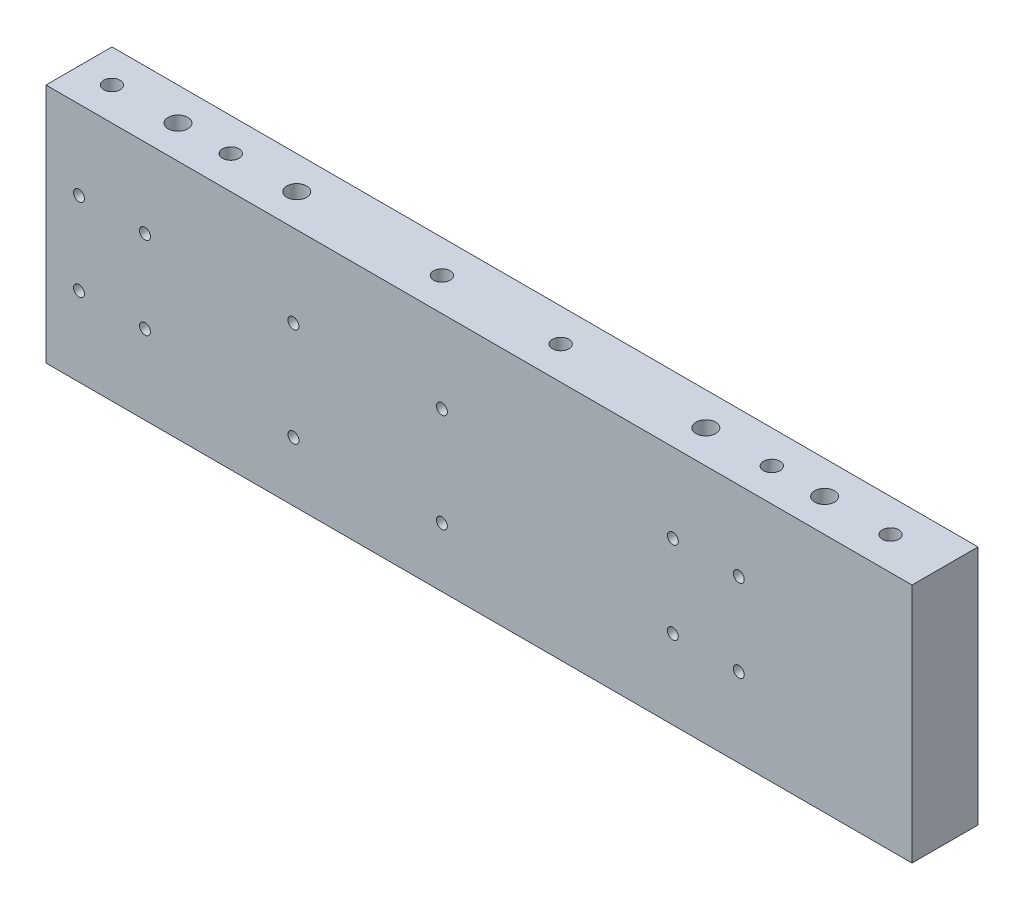
SolidWorks part; units mm, degrees
ref_plane "Front Plane" through (0, 0, 0) normal (0, 0, 1) x (1, 0, 0)
ref_plane "Top Plane" through (0, 0, 0) normal (0, 1, 0) x (1, 0, 0)
ref_plane "Right Plane" through (0, 0, 0) normal (1, 0, 0) x (0, 0, -1)
ref_plane "Ebene1" through (0, 0, 20) normal (0, 0, 1) x (1, 0, 0)
sketch "Skizze1" plane through (0, 0, 20) normal (0, 0, 1) x (1, 0, 0)
  line L0 (110, 0) -> (110, 73)
  line L1 (110, 73) -> (-110, 73)
  line L2 (-110, 73) -> (-110, 0)
  line L3 (-110, 0) -> (110, 0)
  line L4 (0, 73) -> (0, 0) construction
  dimension "D1" = 220
  dimension "D2" = 73
extrude "Aufsatz-Linear austragen1" add sketch "Skizze1" against normal blind 20
hole_wizard "M4 Gewindebohrung1" positions "Skizze5" profile "Skizze4" tap size "M4" standard "DIN" end condition through all
sketch "Skizze5" plane through (0, 0, 20) normal (0, 0, 1) x (1, 0, 0)
  line L0 (10, 48) -> (-35, 48) construction
  line L3 (10, 18) -> (-35, 18) construction
  line L6 (-35, 48) -> (-35, 18) construction
  line L9 (10, 48) -> (10, 18) construction
  line L12 (110, 73) -> (-110, 73) construction
  line L13 (-110, 73) -> (-110, 0) construction
  point P0 (10, 48)
  point P1 (10, 18)
  point P2 (-35, 18)
  point P3 (-35, 48)
  dimension "D1" = 30
  dimension "D2" = 45
  dimension "D3" = 25
  dimension "D4" = 75
sketch "Skizze4" plane through (10, 48, 20) normal (1, 0, 0) x (0, -1, 0)
  line L0 (0, 0) -> (0, 20)
  line L1 (0, 20) -> (1.65, 20)
  line L2 (1.65, 20) -> (1.65, 0)
  line L5 (1.65, 0) -> (0, 0)
  line L11 (0, -6.35) -> (0, 107.95) construction
  dimension "Nenndurchmesser (Haupt)" = 3.3
  dimension "Bohrungstiefe" = 20
hole_wizard "M6 Gewindebohrung2" positions "Skizze7" profile "Skizze6" tap size "M6" standard "DIN"
sketch "Skizze7" plane through (0, 73, 0) normal (0, 1, 0) x (1, 0, 0)
  line L0 (110, -10) -> (-110, -10) construction
  line L1 (110, 0) -> (110, -20) construction
  line L2 (-110, 0) -> (-110, -20) construction
  line L5 (0, -20) -> (0, 0) construction
  line L6 (110, -20) -> (-110, -20) construction
  point P0 (0, -10)
  point P1 (-100, -10)
  point P2 (100, -10)
  dimension "D1" = 200
sketch "Skizze6" plane through (0, 73, 10) normal (1, 0, 0) x (0, 0, 1)
  line L0 (0, 0) -> (0, 18.5022)
  line L1 (0, 18.5022) -> (2.5, 17)
  line L2 (2.5, 17) -> (2.5, 0)
  line L5 (2.5, 0) -> (0, 0)
  line L10 (0, 18.5022) -> (-2.5, 17) construction
  line L11 (0, -6.35) -> (0, 107.95) construction
  dimension "Bohrerdurchmesser" = 5
  dimension "Bohrungstiefe" = 17
  dimension "Spitzenwinkel" = 118
hole_wizard "Ø6.0mm Transitional Stiftloch1" positions "Skizze11" profile "Skizze10" hole size "Ø6.0" standard "DIN"
sketch "Skizze11" plane through (0, 73, 0) normal (0, 1, 0) x (1, 0, 0)
  line L0 (0, 0) -> (0, -20) construction
  line L1 (110, -20) -> (-110, -20) construction
  line L4 (-110, -10) -> (110, -10) construction
  line L5 (-110, 0) -> (-110, -20) construction
  line L6 (110, 0) -> (110, -20) construction
  point P0 (-80, -10)
  point P1 (80, -10)
  dimension "D1" = 160
sketch "Skizze10" plane through (-80, 73, 10) normal (1, 0, 0) x (0, 0, 1)
  line L0 (0, 0) -> (0, 11.8026)
  line L1 (0, 11.8026) -> (3, 10)
  line L2 (3, 10) -> (3, 0)
  line L5 (3, 0) -> (0, 0)
  line L10 (0, 11.8026) -> (-3, 10) construction
  line L11 (0, -6.35) -> (0, 107.95) construction
  dimension "Bohrerdurchmesser" = 6
  dimension "Bohrungstiefe" = 10
  dimension "Spitzenwinkel" = 118
hole_wizard "M6 Gewindebohrung1" positions "Skizze13" profile "Skizze12" tap size "M6" standard "DIN"
sketch "Skizze13" plane through (0, 0, 0) normal (0, -1, 0) x (-1, 0, 0)
  line L0 (110, -10) -> (-110, -10) construction
  line L1 (110, 0) -> (110, -20) construction
  line L2 (-110, 0) -> (-110, -20) construction
  line L5 (0, 0) -> (0, -20) construction
  line L6 (-110, -20) -> (110, -20) construction
  point P0 (100, -10)
  point P1 (0, -10)
  point P2 (-100, -10)
  dimension "D1" = 200
sketch "Skizze12" plane through (-100, 0, 10) normal (1, 0, 0) x (0, 0, -1)
  line L0 (0, 0) -> (0, 18.5022)
  line L1 (0, 18.5022) -> (2.5, 17)
  line L2 (2.5, 17) -> (2.5, 0)
  line L5 (2.5, 0) -> (0, 0)
  line L10 (0, 18.5022) -> (-2.5, 17) construction
  line L11 (0, -6.35) -> (0, 107.95) construction
  dimension "Bohrerdurchmesser" = 5
  dimension "Bohrungstiefe" = 17
  dimension "Spitzenwinkel" = 118
hole_wizard "Ø6.0mm Stiftloch1" positions "Skizze15" profile "Skizze14" hole size "Ø6.0" standard "DIN"
sketch "Skizze15" plane through (0, 0, 0) normal (0, -1, 0) x (-1, 0, 0)
  line L0 (-110, -10) -> (110, -10) construction
  line L1 (-110, 0) -> (-110, -20) construction
  line L2 (110, 0) -> (110, -20) construction
  line L4 (0, 0) -> (0, -20) construction
  line L5 (110, 0) -> (-110, 0) construction
  line L6 (110, -20) -> (-110, -20) construction
  point P0 (-80, -10)
  point P1 (80, -10)
  dimension "D1" = 160
sketch "Skizze14" plane through (80, 0, 10) normal (1, 0, 0) x (0, 0, -1)
  line L0 (0, 0) -> (0, 11.8026)
  line L1 (0, 11.8026) -> (3, 10)
  line L2 (3, 10) -> (3, 0)
  line L5 (3, 0) -> (0, 0)
  line L10 (0, 11.8026) -> (-3, 10) construction
  line L11 (0, -6.35) -> (0, 107.95) construction
  dimension "Bohrerdurchmesser" = 6
  dimension "Bohrungstiefe" = 10
  dimension "Spitzenwinkel" = 118
hole_wizard "M4 Gewindebohrung2" positions "Skizze3" profile "Skizze2" tap size "M4" standard "DIN"
sketch "Skizze3" plane through (0, 0, 20) normal (0, 0, 1) x (1, 0, 0)
  line L0 (0, 73) -> (0, 0) construction
  line L1 (110, 73) -> (-110, 73) construction
  line L4 (-110, 0) -> (110, 0) construction
  line L7 (-80, 73) -> (-80, 0) construction
  line L8 (-100, 73) -> (-100, 0) construction
  line L9 (-80, 49) -> (-100, 49) construction
  line L10 (-110, 36.5) -> (110, 36.5) construction
  line L11 (-110, 73) -> (-110, 0) construction
  line L12 (110, 0) -> (110, 73) construction
  point P8 (-80, 24)
  point P32 (-80, 49)
  point P74 (-100, 24)
  point P75 (-100, 49)
  point P76 (100, 49)
  point P77 (100, 24)
  point P79 (80, 49)
  point P80 (80, 24)
  point P95 (-100, 8) [skipped]
  dimension "D1" = 2
  dimension "D3" = 25
  dimension "D5" = 160
  dimension "D6" = 20
sketch "Skizze2" plane through (-80, 24, 20) normal (1, 0, 0) x (0, -1, 0)
  line L0 (0, 0) -> (0, 20)
  line L1 (0, 20) -> (1.65, 20)
  line L2 (1.65, 20) -> (1.65, 0)
  line L5 (1.65, 0) -> (0, 0)
  line L11 (0, -6.35) -> (0, 107.95) construction
  dimension "Nenndurchmesser (Haupt)" = 3.3
  dimension "Bohrungstiefe" = 20
sketch "Skizze16" plane through (110, 0, 0) normal (1, 0, 0) x (0, 0, -1)
  line L1 (-20, 73) -> (0, 73)
  line L2 (-20, 73) -> (-20, 0)
  line L3 (-20, 0) -> (0, 0)
  line L4 (0, 73) -> (0, 0)
  line L5 (-10, 0) -> (-10, 73) construction
  line L6 (-20, 36.5) -> (0, 36.5) construction
  point P108 (-10, 36.5)
extrude "Aufsatz-Linear austragen2" add sketch "Skizze16" along normal blind 42.5
pattern_linear "Lineares Muster1" count 2 spacing 36 along (1, 0, 0) of "Ø6.0mm Transitional Stiftloch1", "M6 Gewindebohrung2"
